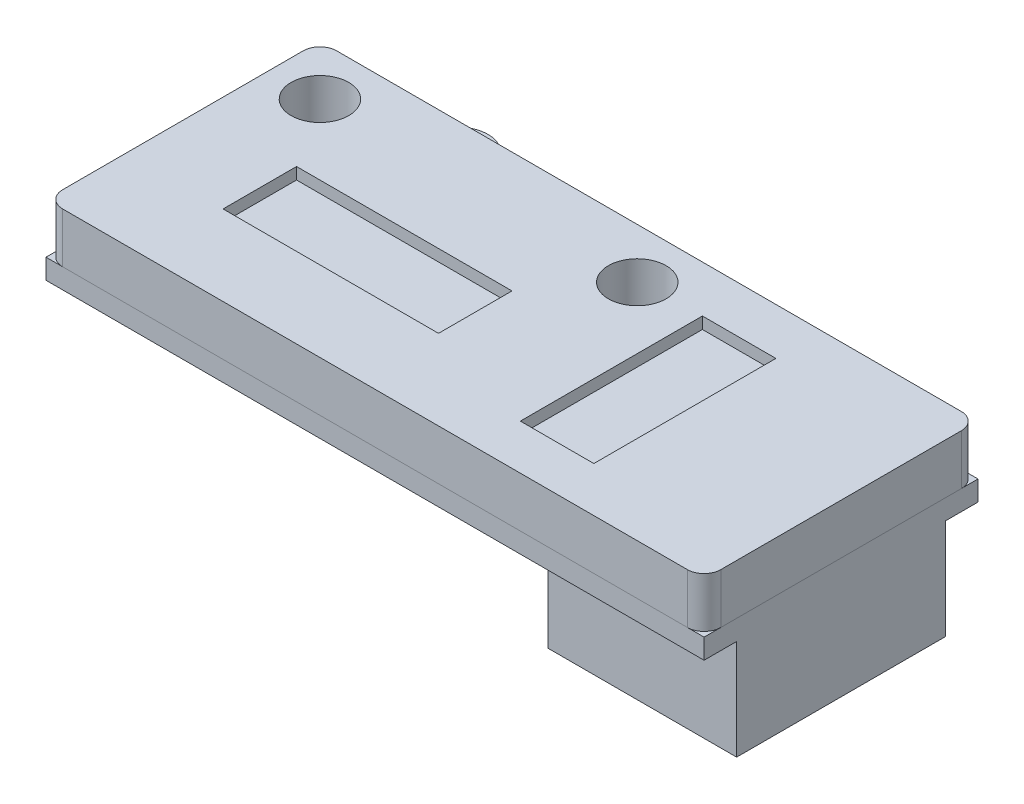
SolidWorks part; units mm, degrees
ref_plane "Front Plane" through (0, 0, 0) normal (0, 0, 1) x (1, 0, 0)
ref_plane "Top Plane" through (0, 0, 0) normal (0, 1, 0) x (1, 0, 0)
ref_plane "Right Plane" through (0, 0, 0) normal (1, 0, 0) x (0, 0, -1)
sketch "Sketch1" plane through (0, 0, 0) normal (0, 1, 0) x (1, 0, 0)
  line L1 (19.7, -8.2) -> (-19.7, -8.2)
  line L2 (19.7, -8.2) -> (19.7, 8.2)
  line L3 (19.7, 8.2) -> (-19.7, 8.2)
  line L4 (-19.7, -8.2) -> (-19.7, 8.2)
  line L5 (0, 8.2) -> (0, -8.2) construction
  line L6 (19.7, 0) -> (-19.7, 0) construction
  circle A0 centre (-16.7, 5.2) radius 1.725
  circle A1 centre (2.3, 5.2) radius 1.725
  point P0 (0, 0)
  dimension "D4" = 3.45
  dimension "D1" = 16.4
  dimension "D2" = 39.4
  dimension "D3" = 19
  dimension "D5" = 3
  dimension "D6" = 3
extrude "Boss-Extrude1" add sketch "Sketch1" along normal blind 1.2
sketch "Sketch2" plane through (0, 1.2, 0) normal (0, 1, 0) x (1, 0, 0)
  line L0 (19.7, -8.2) -> (19.7, 8.2) construction
  line L1 (-13.7, 0.8) -> (-1.2, 0.8)
  line L2 (-13.7, 0.8) -> (-13.7, -3.2)
  line L3 (-13.7, -3.2) -> (-1.2, -3.2)
  line L4 (-1.2, 0.8) -> (-1.2, -3.2)
  line L5 (6.2, 5.2) -> (10.2, 5.2)
  line L6 (6.2, 5.2) -> (6.2, -5.3)
  line L7 (6.2, -5.3) -> (10.2, -5.3)
  line L8 (10.2, 5.2) -> (10.2, -5.3)
  line L9 (19.7, 8.2) -> (-19.7, 8.2) construction
  line L10 (-19.7, 8.2) -> (-19.7, -8.2) construction
  line L11 (-19.7, -8.2) -> (19.7, -8.2) construction
  dimension "D1" = 4
  dimension "D2" = 12.5
  dimension "D3" = 10.5
  dimension "D4" = 9.5
  dimension "D5" = 3
  dimension "D6" = 6
  dimension "D7" = 5
extrude "Boss-Extrude2" add sketch "Sketch2" along normal blind 2.5
sketch "Sketch3" plane through (0, 0, 0) normal (0, -1, 0) x (1, 0, 0)
  line L0 (19.7, 8.2) -> (19.7, -8.2) construction
  line L1 (19.7, 6.25) -> (8.4, 6.25)
  line L2 (19.7, 6.25) -> (19.7, -6.25)
  line L3 (19.7, -6.25) -> (8.4, -6.25)
  line L4 (8.4, 6.25) -> (8.4, -6.25)
  line L5 (19.7, -8.2) -> (-19.7, -8.2) construction
  line L6 (-13.575, -8.2) -> (-0.825, -8.2)
  line L7 (-13.575, -8.2) -> (-13.575, -1.6)
  line L8 (-13.575, -1.6) -> (-0.825, -1.6)
  line L9 (-0.825, -8.2) -> (-0.825, -1.6)
  line L10 (0, 0) -> (8.4, 0) construction
  line L11 (2.3, -5.2) -> (-16.7, -5.2) construction
  line L12 (-7.2, -5.2) -> (-7.2, -1.6) construction
  dimension "D1" = 11.3
  dimension "D2" = 12.5
  dimension "D3" = 6.6
  dimension "D4" = 12.75
extrude "Boss-Extrude3" add sketch "Sketch3" along normal blind 6
ref_plane "Plane1" through (0, -3, 0) normal (0, -1, 0) x (-1, 0, 0)
sketch "Sketch4" plane through (0, -3, 0) normal (0, -1, 0) x (-1, 0, 0)
  line L0 (1.825, 8.2) -> (13.224, 11.95)
  line L1 (13.575, 8.2) -> (0.825, 8.2) construction
  line L2 (9.4425, 13.6) -> (14.0472, 13.6) construction
  line L3 (0.825, 1.6) -> (13.575, 1.6) construction
  line L4 (0.825, 8.2) -> (0.825, 1.6) construction
  line L5 (0.825, 8.2) -> (0.825, 1.6) construction
  line L6 (2.465, 8.2) -> (13.4165, 11.8028)
  line L7 (1.825, 8.2) -> (2.465, 8.2)
  line L8 (16.6277, 12.05) -> (16.825, 12.083)
  line L9 (1.8875, 8.01) -> (13.4165, 11.8028) construction
  arc A0 (13.224, 11.95) -> (16.825, 12.083) centre (15.0331, 11.7832) cw
  arc A1 (13.4165, 11.8028) -> (16.6277, 12.05) centre (15.0331, 11.7832) cw
  dimension "D6" = 1.8168
  dimension "D1" = 12
  dimension "D2" = 3.75
  dimension "D3" = 16
  dimension "D4" = 12
  dimension "D5" = 1
  dimension "D7" = 0.2
extrude "Boss-Extrude4" add sketch "Sketch4" along normal mid plane 4
sketch "Sketch5" plane through (0, 1.2, 0) normal (0, 1, 0) x (1, 0, 0)
  line L4 (-19.7, 8.2) -> (-19.7, -8.2)
  line L5 (-19.7, -8.2) -> (19.7, -8.2)
  line L6 (19.7, -8.2) -> (19.7, 8.2)
  line L7 (19.7, 8.2) -> (-19.7, 8.2)
  line L8 (-19.7, 8.2) -> (-19.7, -8.2)
  line L9 (-19.7, -8.2) -> (19.7, -8.2)
  line L10 (19.7, -8.2) -> (19.7, 8.2)
  line L11 (19.7, 8.2) -> (-19.7, 8.2)
  line L16 (-13.9, 1) -> (-13.9, -3.4)
  line L17 (-13.9, -3.4) -> (-1, -3.4)
  line L18 (-1, -3.4) -> (-1, 1)
  line L19 (-1, 1) -> (-13.9, 1)
  line L20 (-13.9, 1) -> (-13.9, -3.4)
  line L21 (-13.9, -3.4) -> (-1, -3.4)
  line L22 (-1, -3.4) -> (-1, 1)
  line L23 (-1, 1) -> (-13.9, 1)
  line L28 (6, 5.4) -> (6, -5.5)
  line L29 (6, -5.5) -> (10.4, -5.5)
  line L30 (10.4, -5.5) -> (10.4, 5.4)
  line L31 (10.4, 5.4) -> (6, 5.4)
  line L32 (6, 5.4) -> (6, -5.5)
  line L33 (6, -5.5) -> (10.4, -5.5)
  line L34 (10.4, -5.5) -> (10.4, 5.4)
  line L35 (10.4, 5.4) -> (6, 5.4)
  circle A0 centre (2.3, 5.2) radius 1.725 construction
  circle A1 centre (-16.7, 5.2) radius 1.725 construction
  circle A2 centre (2.3, 5.2) radius 1.725
  circle A3 centre (-16.7, 5.2) radius 1.725
  dimension "D1" = 0
  dimension "D2" = 0.2
  dimension "D3" = 0.2
extrude "Boss-Extrude5" add sketch "Sketch5" along normal blind 3 separate body
fillet "Fillet1" radius 1 4 edges at (19.7, 2.7, 8.2) (19.7, 2.7, -8.2) (-19.7, 2.7, 8.2) (-19.7, 2.7, -8.2)
